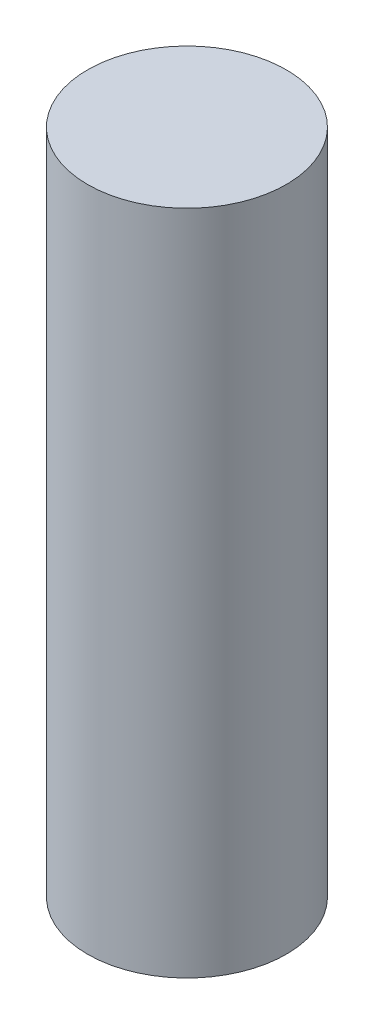
SolidWorks part; units mm, degrees
ref_plane "Front Plane" through (0, 0, 0) normal (0, 0, 1) x (1, 0, 0)
ref_plane "Top Plane" through (0, 0, 0) normal (0, 1, 0) x (1, 0, 0)
ref_plane "Right Plane" through (0, 0, 0) normal (1, 0, 0) x (0, 0, -1)
sketch "Sketch1" plane through (0, 0, 0) normal (0, 1, 0) x (1, 0, 0)
  circle A0 centre (0, 0) radius 4.025
  dimension "D1" = 8.05
extrude "Boss-Extrude1" add sketch "Sketch1" along normal blind 27
